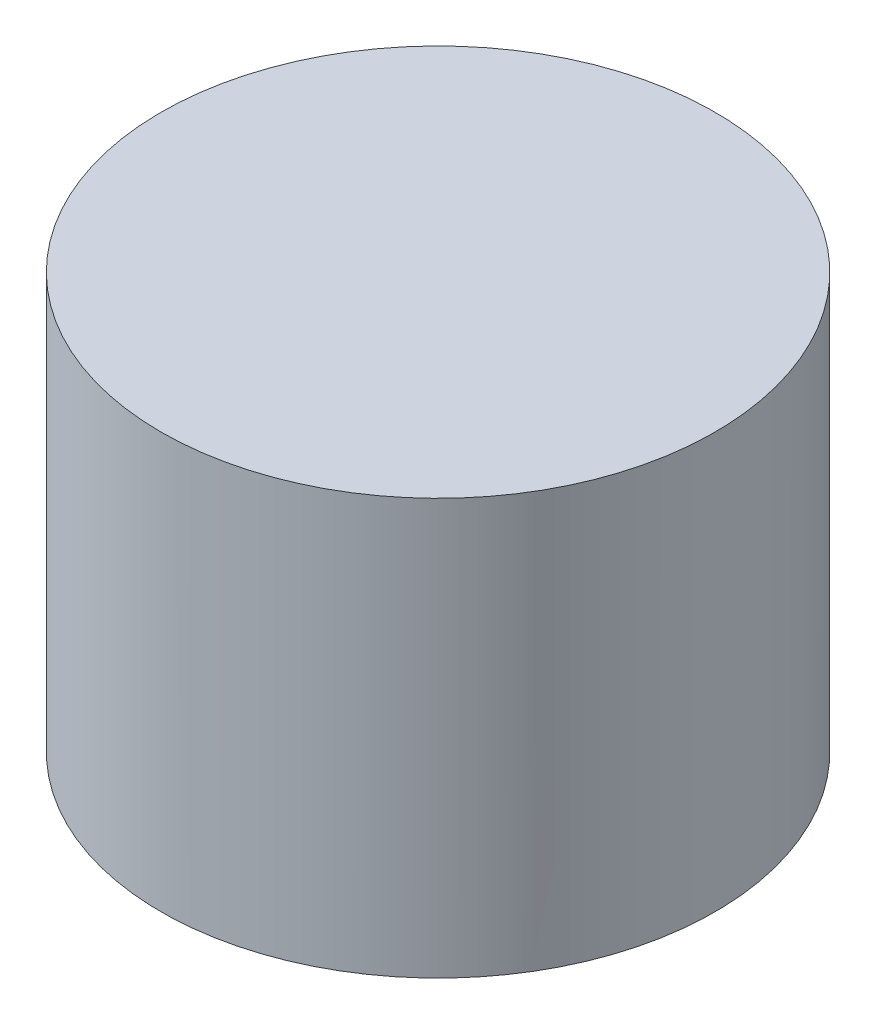
SolidWorks part; units mm, degrees
ref_plane "Front Plane" through (0, 0, 0) normal (0, 0, 1) x (1, 0, 0)
ref_plane "Top Plane" through (0, 0, 0) normal (0, 1, 0) x (1, 0, 0)
ref_plane "Right Plane" through (0, 0, 0) normal (1, 0, 0) x (0, 0, -1)
sketch "Sketch1" plane through (0, 0, 0) normal (0, 1, 0) x (1, 0, 0)
  circle A0 centre (0, 0) radius 20
extrude "Boss-Extrude1" add sketch "Sketch1" along normal blind 10
sketch "Sketch2" plane through (0, 10, 0) normal (0, 1, 0) x (1, 0, 0)
  line L1 (10.0484, -5.6888) -> (9.9509, 5.8578)
  line L2 (9.9509, 5.8578) -> (-0.0976, 11.5466)
  line L3 (-0.0976, 11.5466) -> (-10.0484, 5.6888)
  line L4 (-10.0484, 5.6888) -> (-9.9509, -5.8578)
  line L5 (-9.9509, -5.8578) -> (0.0976, -11.5466)
  line L6 (0.0976, -11.5466) -> (10.0484, -5.6888)
  circle A0 centre (0, 0) radius 10 construction
  dimension "D1" = 20
extrude "Cut-Extrude2" cut sketch "Sketch2" against normal blind 5
ref_plane "Plane2" through (0, 10, 0) normal (0, 1, 0) x (1, 0, 0)
sketch "Sketch5" plane through (0, 10, 0) normal (0, 1, 0) x (1, 0, 0)
  line L0 (-9.9509, -5.8578) -> (0.0976, -11.5466) construction
  line L1 (0.0976, -11.5466) -> (10.0484, -5.6888) construction
  line L2 (10.0484, -5.6888) -> (9.9509, 5.8578) construction
  line L3 (9.9509, 5.8578) -> (-0.0976, 11.5466) construction
  line L4 (-0.0976, 11.5466) -> (-10.0484, 5.6888) construction
  line L5 (-10.0484, 5.6888) -> (-9.9509, -5.8578) construction
  line L6 (-9.9509, -5.8578) -> (0.0976, -11.5466)
  line L7 (0.0976, -11.5466) -> (10.0484, -5.6888)
  line L8 (10.0484, -5.6888) -> (9.9509, 5.8578)
  line L9 (9.9509, 5.8578) -> (-0.0976, 11.5466)
  line L10 (-0.0976, 11.5466) -> (-10.0484, 5.6888)
  line L11 (-10.0484, 5.6888) -> (-9.9509, -5.8578)
  circle A0 centre (0, 0) radius 20 construction
  circle A1 centre (0, 0) radius 20
extrude "Boss-Extrude3" add sketch "Sketch5" along normal blind 15
sketch "Sketch6" plane through (0, 25, 0) normal (0, 1, 0) x (1, 0, 0)
  circle A0 centre (0, 0) radius 20 construction
  circle A1 centre (0, 0) radius 20
extrude "Boss-Extrude4" add sketch "Sketch6" along normal blind 5
sketch "Sketch7" plane through (0, 0, 0) normal (0, -1, 0) x (1, 0, 0)
  circle A0 centre (0, 0) radius 7.5
extrude "Cut-Extrude3" cut sketch "Sketch7" against normal blind 15
sketch "Sketch8" plane through (0, 0, 0) normal (0, 0, 1) x (1, 0, 0)
  line L0 (0, 0) -> (0, 30) construction
  line L1 (20, 30) -> (-20, 30) construction
  line L2 (22, 0) -> (-22, 0) construction
  line L4 (-6.5, 15) -> (-6.5, 0)
  line L5 (-6.5, 0) -> (6.5, 0)
  line L6 (6.5, 15) -> (6.5, 0)
  line L7 (-6.5, 15) -> (6.5, 0) construction
  line L8 (-6.5, 0) -> (6.5, 15) construction
  line L9 (6.5, 15) -> (12.5, 15)
  line L10 (-12.5, 25) -> (12.5, 25)
  line L11 (-12.5, 25) -> (-12.5, 15)
  line L12 (-12.5, 15) -> (-6.5, 15)
  line L13 (12.5, 25) -> (12.5, 15)
  line L14 (-12.5, 25) -> (12.5, 15) construction
  line L15 (-12.5, 15) -> (12.5, 25) construction
  point P5 (0, 7.5)
  point P12 (0, 20)
  dimension "D1" = 13
  dimension "D3" = 25
  dimension "D4" = 10
extrude "Cut-Extrude4" cut sketch "Sketch8" against normal through all
